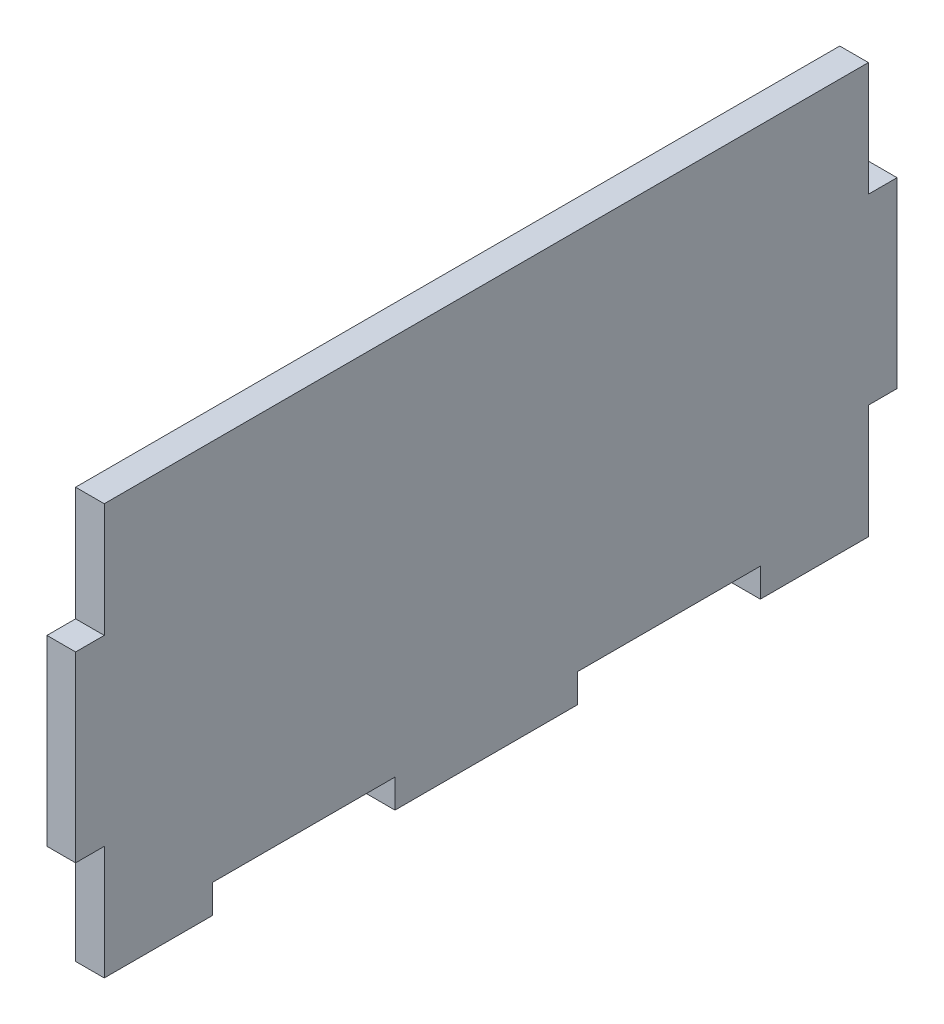
SolidWorks part; units mm, degrees
ref_plane "Front Plane" through (0, 0, 0) normal (0, 0, 1) x (1, 0, 0)
ref_plane "Top Plane" through (0, 0, 0) normal (0, 1, 0) x (1, 0, 0)
ref_plane "Right Plane" through (0, 0, 0) normal (1, 0, 0) x (0, 0, -1)
sketch "Sketch1" plane through (0, 0, 0) normal (1, 0, 0) x (0, 0, -1)
  line L0 (17.319, -27.2211) -> (17.319, -39.1586)
  line L1 (17.319, -39.1586) -> (14.319, -39.1586)
  line L2 (14.319, -39.1586) -> (14.319, -58.2836)
  line L3 (14.319, -58.2836) -> (17.319, -58.2836)
  line L4 (17.319, -58.2836) -> (17.319, -70.2211)
  line L5 (17.319, -70.2211) -> (28.6315, -70.2211)
  line L6 (28.6315, -70.2211) -> (28.6315, -67.2211)
  line L7 (28.6315, -67.2211) -> (47.7565, -67.2211)
  line L8 (47.7565, -67.2211) -> (47.7565, -70.2211)
  line L9 (47.7565, -70.2211) -> (66.8815, -70.2211)
  line L10 (66.8815, -70.2211) -> (66.8815, -67.2211)
  line L11 (66.8815, -67.2211) -> (86.0065, -67.2211)
  line L12 (86.0065, -67.2211) -> (86.0065, -70.2211)
  line L13 (86.0065, -70.2211) -> (97.319, -70.2211)
  line L14 (97.319, -70.2211) -> (97.319, -58.2836)
  line L15 (97.319, -58.2836) -> (100.319, -58.2836)
  line L16 (100.319, -58.2836) -> (100.319, -39.1586)
  line L17 (100.319, -39.1586) -> (97.319, -39.1586)
  line L18 (97.319, -39.1586) -> (97.319, -27.2211)
  line L19 (97.319, -27.2211) -> (17.319, -27.2211)
extrude "Boss-Extrude1" add sketch "Sketch1" along normal blind 3
